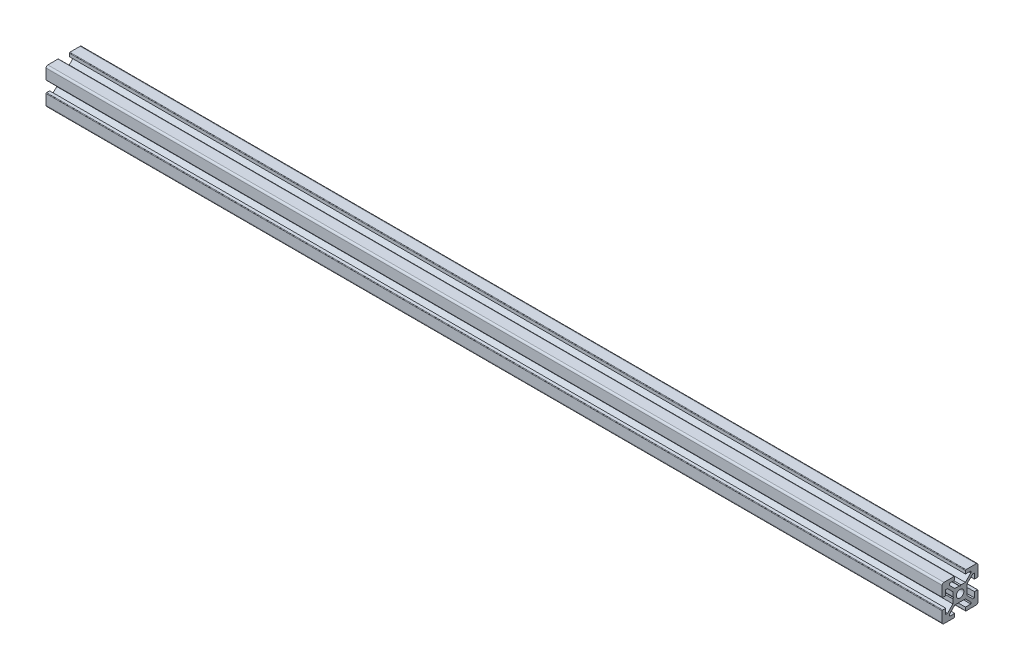
SolidWorks part; units mm, degrees
ref_plane "Front Plane" through (0, 0, 0) normal (0, 0, 1) x (1, 0, 0)
ref_plane "Top Plane" through (0, 0, 0) normal (0, 1, 0) x (1, 0, 0)
ref_plane "Right Plane" through (0, 0, 0) normal (1, 0, 0) x (0, 0, -1)
sketch "Sketch1" plane through (0, 0, 0) normal (1, 0, 0) x (0, 0, -1)
  line L0 (-9.9351, 3.3809) -> (-9.9351, 9.0809)
  line L1 (-8.9351, 10.0809) -> (-3.2351, 10.0809)
  line L2 (-2.9351, 9.7809) -> (-2.9351, 8.0809)
  line L3 (-2.9351, 8.0809) -> (-5.9351, 8.0809)
  line L4 (-5.9351, 8.0809) -> (-5.9351, 7.1416)
  line L5 (-5.9351, 7.1416) -> (-2.8744, 4.0809)
  line L6 (-2.8744, 4.0809) -> (-0.4547, 4.0809)
  line L7 (-0.4547, 4.0809) -> (0.0649, 3.7809)
  line L8 (0.0649, 3.7809) -> (0.5845, 4.0809)
  line L9 (0.5845, 4.0809) -> (3.0043, 4.0809)
  line L10 (3.0043, 4.0809) -> (6.0649, 7.1416)
  line L11 (6.0649, 7.1416) -> (6.0649, 8.0809)
  line L12 (6.0649, 8.0809) -> (3.0649, 8.0809)
  line L13 (3.0649, 8.0809) -> (3.0649, 9.7809)
  line L14 (3.3649, 10.0809) -> (9.0649, 10.0809)
  line L15 (10.0649, 9.0809) -> (10.0649, 3.3809)
  line L16 (9.7649, 3.0809) -> (8.0649, 3.0809)
  line L17 (8.0649, 3.0809) -> (8.0649, 6.0809)
  line L18 (8.0649, 6.0809) -> (7.1256, 6.0809)
  line L19 (7.1256, 6.0809) -> (4.0649, 3.0203)
  line L20 (4.0649, 3.0203) -> (4.0649, 0.6005)
  line L21 (4.0649, 0.6005) -> (3.7649, 0.0809)
  line L22 (3.7649, 0.0809) -> (4.0649, -0.4387)
  line L23 (4.0649, -0.4387) -> (4.0649, -2.8584)
  line L24 (4.0649, -2.8584) -> (7.1256, -5.9191)
  line L25 (7.1256, -5.9191) -> (8.0649, -5.9191)
  line L26 (8.0649, -5.9191) -> (8.0649, -2.9191)
  line L27 (8.0649, -2.9191) -> (9.7649, -2.9191)
  line L28 (10.0649, -3.2191) -> (10.0649, -8.9191)
  line L29 (9.0649, -9.9191) -> (3.3649, -9.9191)
  line L30 (3.0649, -9.6191) -> (3.0649, -7.919)
  line L31 (3.0649, -7.919) -> (6.0649, -7.919)
  line L32 (6.0649, -7.919) -> (6.0649, -6.9797)
  line L33 (6.0649, -6.9797) -> (3.0043, -3.9191)
  line L34 (3.0043, -3.9191) -> (0.5845, -3.9191)
  line L35 (0.5845, -3.9191) -> (0.0649, -3.6191)
  line L36 (0.0649, -3.6191) -> (-0.4547, -3.9191)
  line L37 (-0.4547, -3.9191) -> (-2.8744, -3.9191)
  line L38 (-2.8744, -3.9191) -> (-5.9351, -6.9797)
  line L39 (-5.9351, -6.9797) -> (-5.9351, -7.919)
  line L40 (-5.9351, -7.919) -> (-2.9351, -7.919)
  line L41 (-2.9351, -7.919) -> (-2.9351, -9.6191)
  line L42 (-3.2351, -9.9191) -> (-8.9351, -9.9191)
  line L43 (-9.9351, -8.9191) -> (-9.9351, -3.2191)
  line L44 (-9.6351, -2.9191) -> (-7.9351, -2.9191)
  line L45 (-7.9351, -2.9191) -> (-7.9351, -5.9191)
  line L46 (-7.9351, -5.9191) -> (-6.9958, -5.9191)
  line L47 (-6.9958, -5.9191) -> (-3.9351, -2.8584)
  line L48 (-3.9351, -2.8584) -> (-3.9351, -0.4387)
  line L49 (-3.9351, -0.4387) -> (-3.6351, 0.0809)
  line L50 (-3.6351, 0.0809) -> (-3.9351, 0.6005)
  line L51 (-3.9351, 0.6005) -> (-3.9351, 3.0203)
  line L52 (-3.9351, 3.0203) -> (-6.9958, 6.0809)
  line L53 (-6.9958, 6.0809) -> (-7.9351, 6.0809)
  line L54 (-7.9351, 6.0809) -> (-7.9351, 3.0809)
  line L55 (-7.9351, 3.0809) -> (-9.6351, 3.0809)
  arc A0 (-9.9351, 9.0809) -> (-8.9351, 10.0809) centre (-8.9351, 9.0809) cw
  arc A1 (-3.2351, 10.0809) -> (-2.9351, 9.7809) centre (-3.2351, 9.7809) cw
  arc A2 (3.0649, 9.7809) -> (3.3649, 10.0809) centre (3.3649, 9.7809) cw
  arc A3 (9.0649, 10.0809) -> (10.0649, 9.0809) centre (9.0649, 9.0809) cw
  arc A4 (10.0649, 3.3809) -> (9.7649, 3.0809) centre (9.7649, 3.3809) cw
  arc A5 (9.7649, -2.9191) -> (10.0649, -3.2191) centre (9.7649, -3.2191) cw
  arc A6 (10.0649, -8.9191) -> (9.0649, -9.9191) centre (9.0649, -8.9191) cw
  arc A7 (3.0649, -9.6191) -> (3.3649, -9.9191) centre (3.3649, -9.6191) ccw
  arc A8 (-2.9351, -9.6191) -> (-3.2351, -9.9191) centre (-3.2351, -9.6191) cw
  arc A9 (-9.9351, -8.9191) -> (-8.9351, -9.9191) centre (-8.9351, -8.9191) ccw
  arc A10 (-9.6351, -2.9191) -> (-9.9351, -3.2191) centre (-9.6351, -3.2191) ccw
  arc A11 (-9.9351, 3.3809) -> (-9.6351, 3.0809) centre (-9.6351, 3.3809) ccw
  circle A12 centre (0.0649, 0.0809) radius 2.1
extrude "Boss-Extrude1" add sketch "Sketch1" along normal blind 500
